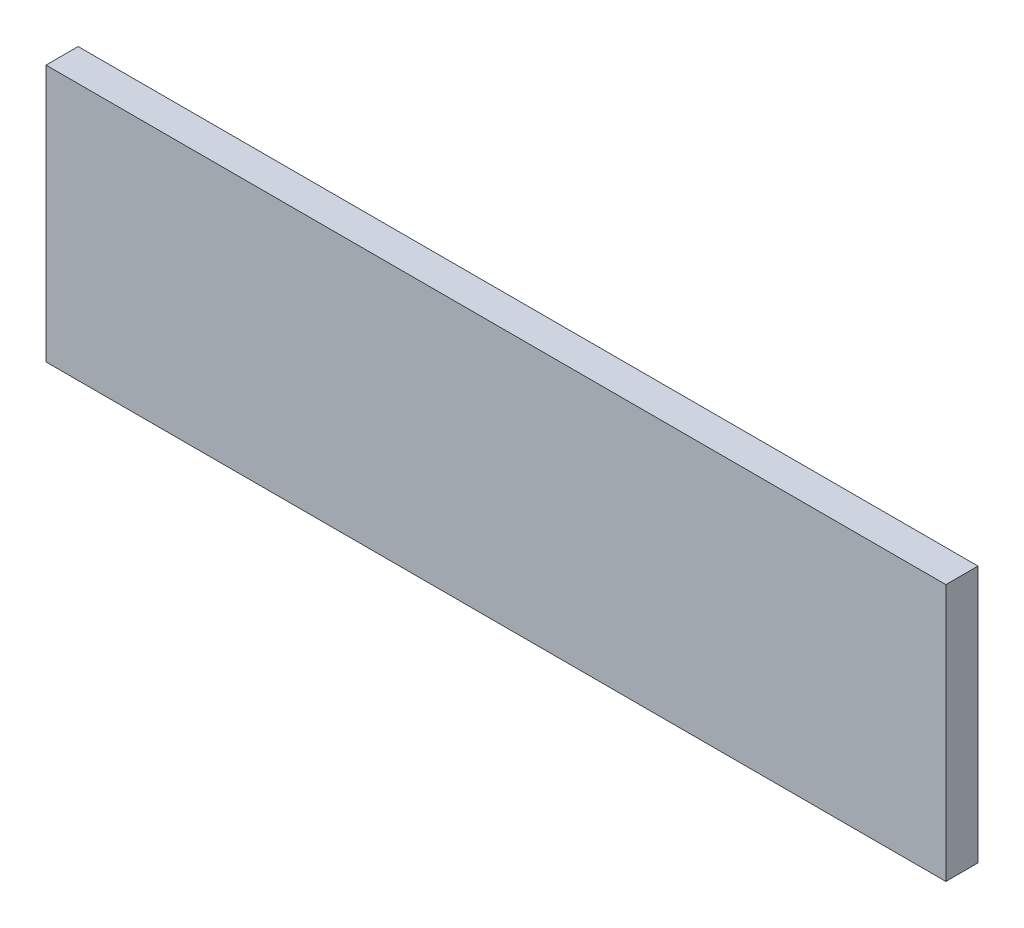
SolidWorks part; units mm, degrees
ref_plane "Plan de face" through (0, 0, 0) normal (0, 0, 1) x (1, 0, 0)
ref_plane "Plan de dessus" through (0, 0, 0) normal (0, 1, 0) x (1, 0, 0)
ref_plane "Plan de droite" through (0, 0, 0) normal (1, 0, 0) x (0, 0, -1)
sketch "Esquisse1" plane through (0, 0, 0) normal (0, 0, 1) x (1, 0, 0)
  line L1 (0, 0) -> (355.6, 0)
  line L2 (0, 0) -> (0, 101.6)
  line L3 (0, 101.6) -> (355.6, 101.6)
  line L4 (355.6, 0) -> (355.6, 101.6)
  dimension "D1" = 355.6
  dimension "D2" = 101.6
extrude "Boss.-Extru.1" add sketch "Esquisse1" against normal blind 12.7
